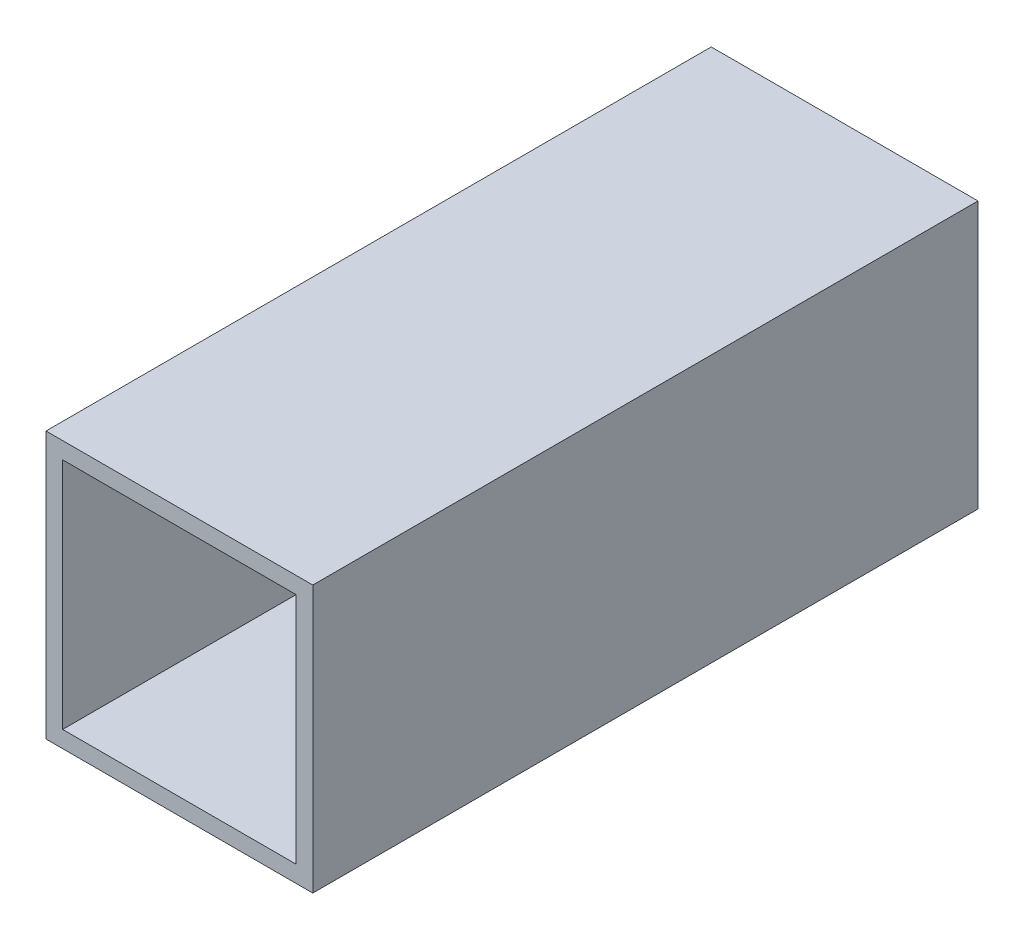
SolidWorks part; units mm, degrees
ref_plane "Alzado" through (0, 0, 0) normal (0, 0, 1) x (1, 0, 0)
ref_plane "Planta" through (0, 0, 0) normal (0, 1, 0) x (1, 0, 0)
ref_plane "Vista lateral" through (0, 0, 0) normal (1, 0, 0) x (0, 0, -1)
sketch "Croquis2" plane through (0, 0, 0) normal (0, 0, 1) x (1, 0, 0)
  line L0 (4.7625, -4.7625) -> (71.4375, -4.7625)
  line L1 (0, 0) -> (76.2, 0)
  line L2 (0, 0) -> (0, -76.2)
  line L3 (0, -76.2) -> (76.2, -76.2)
  line L4 (76.2, 0) -> (76.2, -76.2)
  line L5 (71.4375, -4.7625) -> (71.4375, -71.4375)
  line L6 (4.7625, -71.4375) -> (71.4375, -71.4375)
  line L7 (4.7625, -4.7625) -> (4.7625, -71.4375)
  dimension "D1" = 76.2
  dimension "D2" = 76.2
  dimension "D3" = 4.7625
extrude "Saliente-Extruir1" add sketch "Croquis2" against normal blind 190
